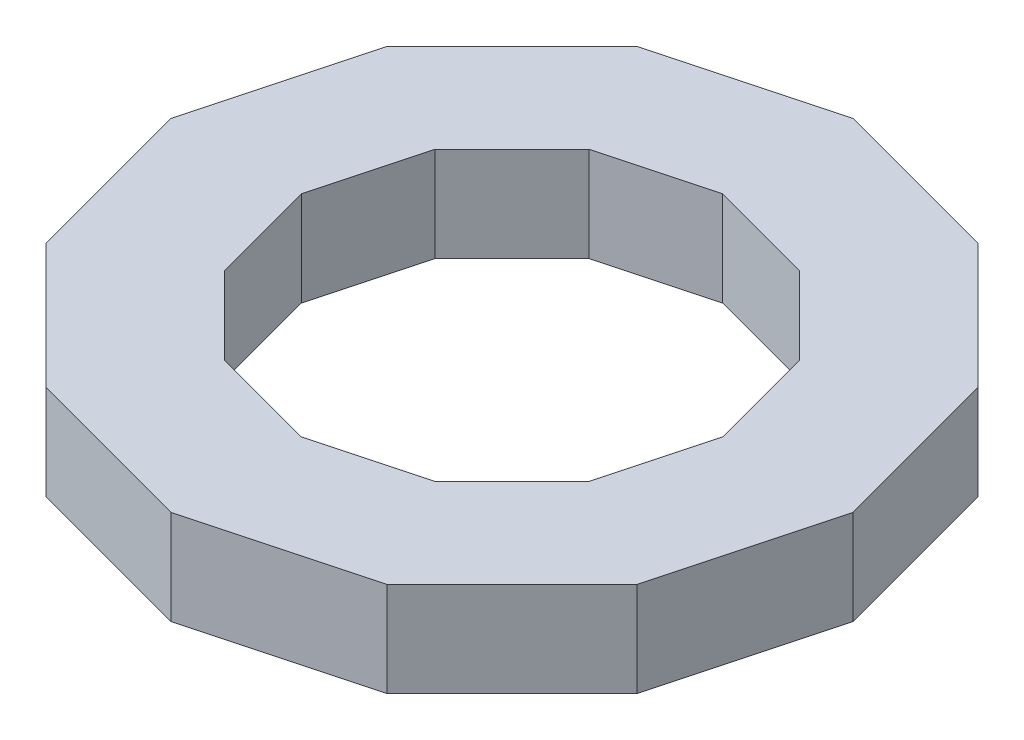
SolidWorks part; units mm, degrees
ref_plane "Front Plane" through (0, 0, 0) normal (0, 0, 1) x (1, 0, 0)
ref_plane "Top Plane" through (0, 0, 0) normal (0, 1, 0) x (1, 0, 0)
ref_plane "Right Plane" through (0, 0, 0) normal (1, 0, 0) x (0, 0, -1)
sketch "Sketch1" plane through (0, 0, 0) normal (0, 1, 0) x (1, 0, 0)
  line L0 (0, 0) -> (42.4006, 0) construction
  line L1 (42.4006, 0) -> (36.72, 21.2003)
  line L2 (36.72, 21.2003) -> (21.2003, 36.72)
  line L3 (21.2003, 36.72) -> (0, 42.4006)
  line L4 (0, 42.4006) -> (-21.2003, 36.72)
  line L5 (-21.2003, 36.72) -> (-36.72, 21.2003)
  line L6 (-36.72, 21.2003) -> (-42.4006, 0)
  line L7 (-42.4006, 0) -> (-36.72, -21.2003)
  line L8 (-36.72, -21.2003) -> (-21.2003, -36.72)
  line L9 (-21.2003, -36.72) -> (0, -42.4006)
  line L10 (0, -42.4006) -> (21.2003, -36.72)
  line L11 (21.2003, -36.72) -> (36.72, -21.2003)
  line L12 (36.72, -21.2003) -> (42.4006, 0)
  line L13 (68.6966, 0) -> (59.493, 34.3483)
  line L14 (59.493, 34.3483) -> (34.3483, 59.493)
  line L15 (34.3483, 59.493) -> (0, 68.6966)
  line L16 (0, 68.6966) -> (-34.3483, 59.493)
  line L17 (-34.3483, 59.493) -> (-59.493, 34.3483)
  line L18 (-59.493, 34.3483) -> (-68.6966, 0)
  line L19 (-68.6966, 0) -> (-59.493, -34.3483)
  line L20 (-59.493, -34.3483) -> (-34.3483, -59.493)
  line L21 (-34.3483, -59.493) -> (0, -68.6966)
  line L22 (0, -68.6966) -> (34.3483, -59.493)
  line L23 (34.3483, -59.493) -> (59.493, -34.3483)
  line L24 (59.493, -34.3483) -> (68.6966, 0)
  line L25 (59.493, 34.3483) -> (36.72, 21.2003) construction
  circle A0 centre (0, 0) radius 40.9559 construction
  circle A1 centre (0, 0) radius 66.3559 construction
  dimension "D1" = 25.4
  dimension "D2" = 35.56
  dimension "D3" = 105
  dimension "D4" = 66.3559
extrude "Boss-Extrude1" add sketch "Sketch1" along normal blind 19.05
